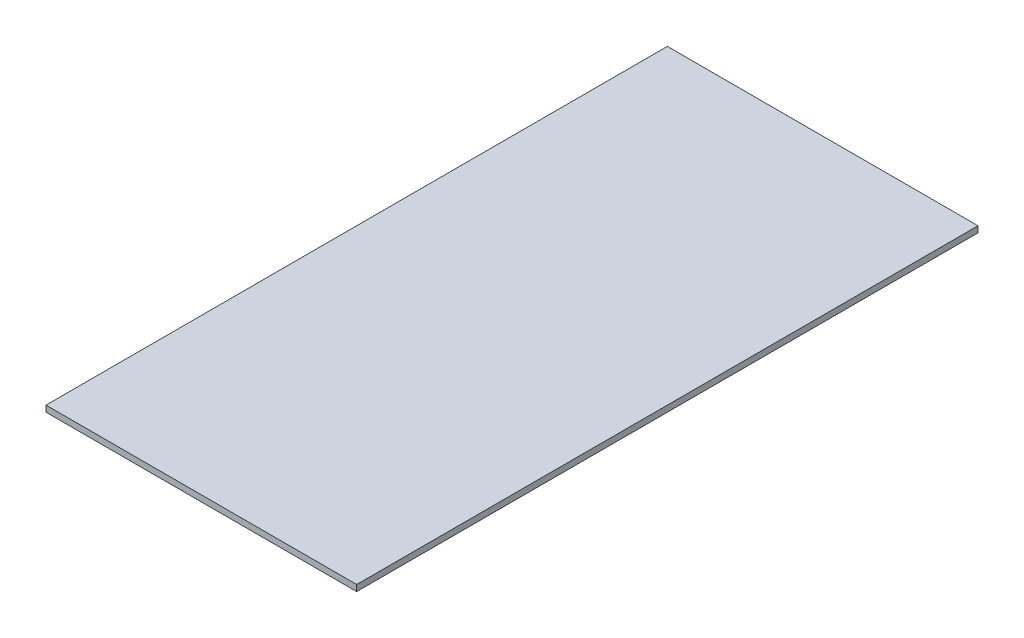
SolidWorks part; units mm, degrees
ref_plane "Front Plane" through (0, 0, 0) normal (0, 0, 1) x (1, 0, 0)
ref_plane "Top Plane" through (0, 0, 0) normal (0, 1, 0) x (1, 0, 0)
ref_plane "Right Plane" through (0, 0, 0) normal (1, 0, 0) x (0, 0, -1)
sketch "Sketch2" plane through (0, 0, 0) normal (0, 1, 0) x (1, 0, 0)
  line L1 (-152.4, -304.8) -> (152.4, -304.8)
  line L2 (-152.4, -304.8) -> (-152.4, 304.8)
  line L3 (-152.4, 304.8) -> (152.4, 304.8)
  line L4 (152.4, -304.8) -> (152.4, 304.8)
  line L5 (-152.4, -304.8) -> (152.4, 304.8) construction
  line L6 (-152.4, 304.8) -> (152.4, -304.8) construction
  point P0 (0, 0)
  dimension "D1" = 304.8
  dimension "D2" = 609.6
extrude "Boss-Extrude1" add sketch "Sketch2" along normal mid plane 6.0452
